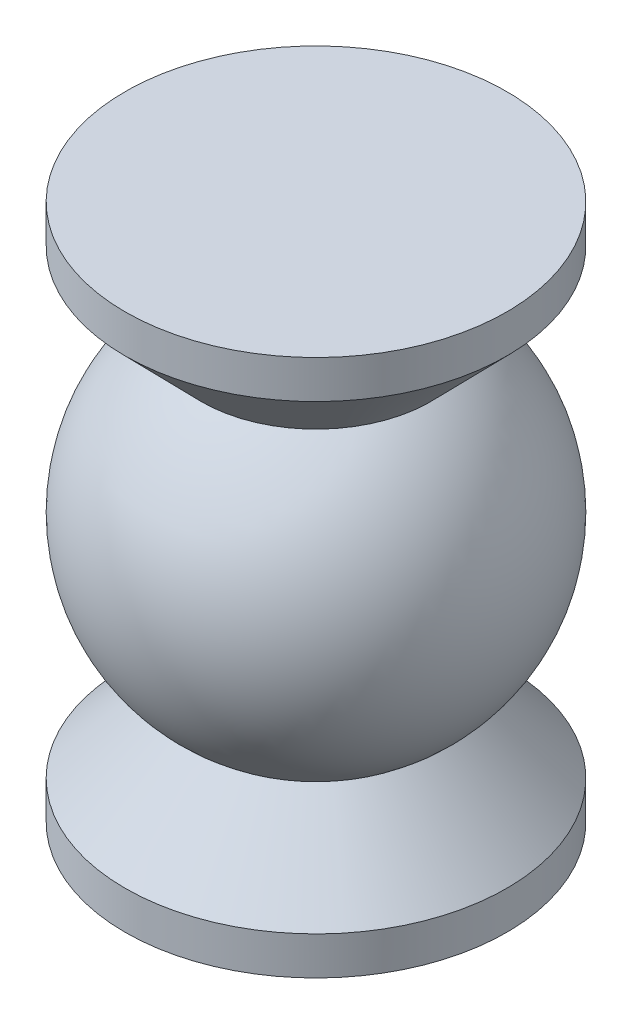
SolidWorks part; units mm, degrees
material "ABS"
ref_plane "Front Plane" through (0, 0, 0) normal (0, 0, 1) x (1, 0, 0)
ref_plane "Top Plane" through (0, 0, 0) normal (0, 1, 0) x (1, 0, 0)
ref_plane "Right Plane" through (0, 0, 0) normal (1, 0, 0) x (0, 0, -1)
sketch "草图1" plane through (0, 0, 0) normal (0, 0, 1) x (1, 0, 0)
  line L0 (0, 19.6169) -> (0, -23.5497) construction
  line L1 (0, 19.6169) -> (-25, 19.6169)
  line L2 (-25, 19.6169) -> (-25, 14.6169)
  line L3 (0, 19.6169) -> (0, -50.7831)
  line L5 (-25, 14.6169) -> (-15, 4.4169)
  line L6 (0, -15.5831) -> (44.3776, -15.5831) construction
  line L7 (-25, -45.7831) -> (-15, -35.5831)
  line L10 (-25, -50.7831) -> (-25, -45.7831)
  line L11 (0, -50.7831) -> (-25, -50.7831)
  line L12 (0, -23.5497) -> (0, -50.7831) construction
  arc A0 (-15, 4.4169) -> (-15, -35.5831) centre (0, -15.5831) ccw
  dimension "D3" = 50
  dimension "D1" = 25
  dimension "D2" = 5
  dimension "D5" = 35.2
revolve "旋转1" add sketch "草图1" angle 360 about L3
shell "抽壳1" [suppressed] thickness 3
sketch "草图2" [suppressed] plane through (0, 22.6169, 0) normal (0, 1, 0) x (1, 0, 0)
  line L0 (0, 0) -> (0, 48.3773) construction
  line L1 (0, 36.3939) -> (-18.6872, -21.1194)
  line L2 (0, 36.3939) -> (18.6872, -21.1194)
  circle A0 centre (0, 0) radius 28.2 construction
  arc A1 (-18.6872, -21.1194) -> (18.6872, -21.1194) centre (0, 0) ccw
  dimension "D1" = 18
